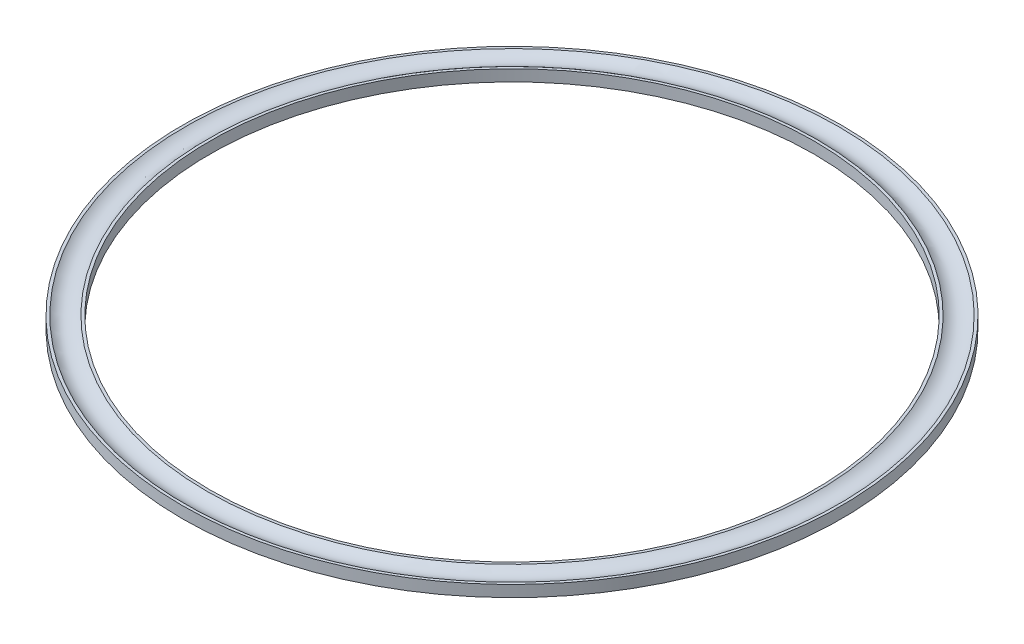
SolidWorks part; units mm, degrees
ref_plane "Front" through (0, 0, 0) normal (0, 0, 1) x (1, 0, 0)
ref_plane "Top" through (0, 0, 0) normal (0, 1, 0) x (1, 0, 0)
ref_plane "Right" through (0, 0, 0) normal (1, 0, 0) x (0, 0, -1)
sketch "Sketch1" plane through (0, 0, 0) normal (0, 0, 1) x (1, 0, 0)
  line L0 (-51.1556, 0) -> (51.1556, 0) construction
  line L1 (55.8038, -0.9652) -> (55.8038, 0.9652)
  line L2 (55.8038, 0.9652) -> (51.1556, 0.9652) construction
  line L3 (0, -11.4126) -> (0, 23.1775) construction
  line L4 (0, -0.6845) -> (0, 0.6845) construction
  line L5 (51.1556, 0.9652) -> (51.6204, 0.9652)
  line L6 (55.8038, -0.9652) -> (51.1556, -0.9652)
  line L7 (51.1556, 0.9652) -> (51.1556, -0.9652)
  line L8 (55.8038, 0.9652) -> (55.339, 0.9652)
  arc A0 (51.6204, 0.9652) -> (55.339, 0.9652) centre (53.4797, 3.2298) ccw
  point P4 (51.1556, 0)
  point P13 (53.4797, 0.2997)
  dimension "D1" = 0.6655
  dimension "D2" = 0.4648
revolve "Revolve2" add sketch "Sketch1" angle 360 about L3
sketch "Sketch3" plane through (0, -0.9652, 0) normal (0, -1, 0) x (1, 0, 0)
  line L0 (51.1556, 0) -> (-51.1556, 0) construction
  circle A0 centre (0, 0) radius 51.1556 construction
  dimension "D1" = 102.3112
equation "\"D2@Sketch1\" = \"Wd@Sketch1\"/10"
